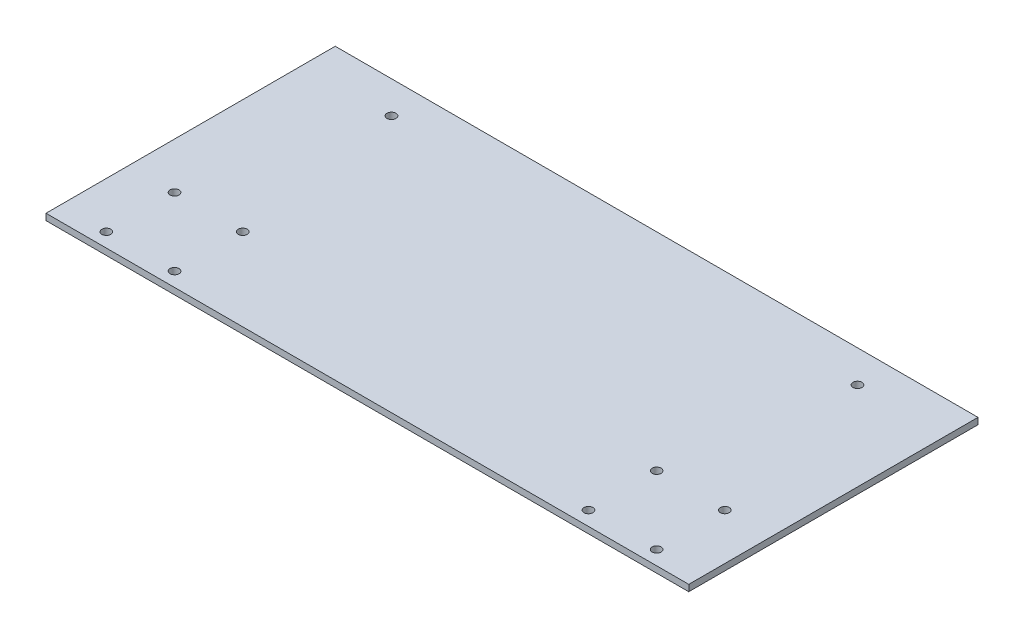
SolidWorks part; units mm, degrees
ref_plane "Front Plane" through (0, 0, 0) normal (0, 0, 1) x (1, 0, 0)
ref_plane "Top Plane" through (0, 0, 0) normal (0, 1, 0) x (1, 0, 0)
ref_plane "Right Plane" through (0, 0, 0) normal (1, 0, 0) x (0, 0, -1)
sketch "Sketch2" plane through (0, 0, 0) normal (0, 1, 0) x (1, 0, 0)
  line L0 (0, -57.15) -> (0, 57.15) construction
  line L1 (-127, -57.15) -> (127, -57.15)
  line L2 (-127, -57.15) -> (-127, 57.15)
  line L3 (-127, 57.15) -> (127, 57.15)
  line L4 (127, -57.15) -> (127, 57.15)
  line L5 (-127, -57.15) -> (127, 57.15) construction
  line L6 (-127, 57.15) -> (127, -57.15) construction
  line L7 (0, 57.15) -> (0, 44.45) construction
  line L8 (92.075, 44.45) -> (-92.075, 44.45) construction
  circle A0 centre (-108.7204, -24.6296) radius 1.778
  circle A1 centre (-81.7796, -24.6296) radius 1.778
  circle A2 centre (-108.7204, -51.5704) radius 1.778
  circle A3 centre (108.7204, -24.6296) radius 1.778
  circle A4 centre (81.7796, -24.6296) radius 1.778
  circle A5 centre (108.7204, -51.5704) radius 1.778
  circle A6 centre (81.7796, -51.5704) radius 1.778
  circle A7 centre (-81.7796, -51.5704) radius 1.778
  circle A8 centre (-92.075, 44.45) radius 1.778
  circle A9 centre (92.075, 44.45) radius 1.778
  point P0 (0, 0)
  point P33 (0, 0)
  point P37 (0, 44.45)
extrude "Boss-Extrude1" add sketch "Sketch2" along normal blind 2.54
